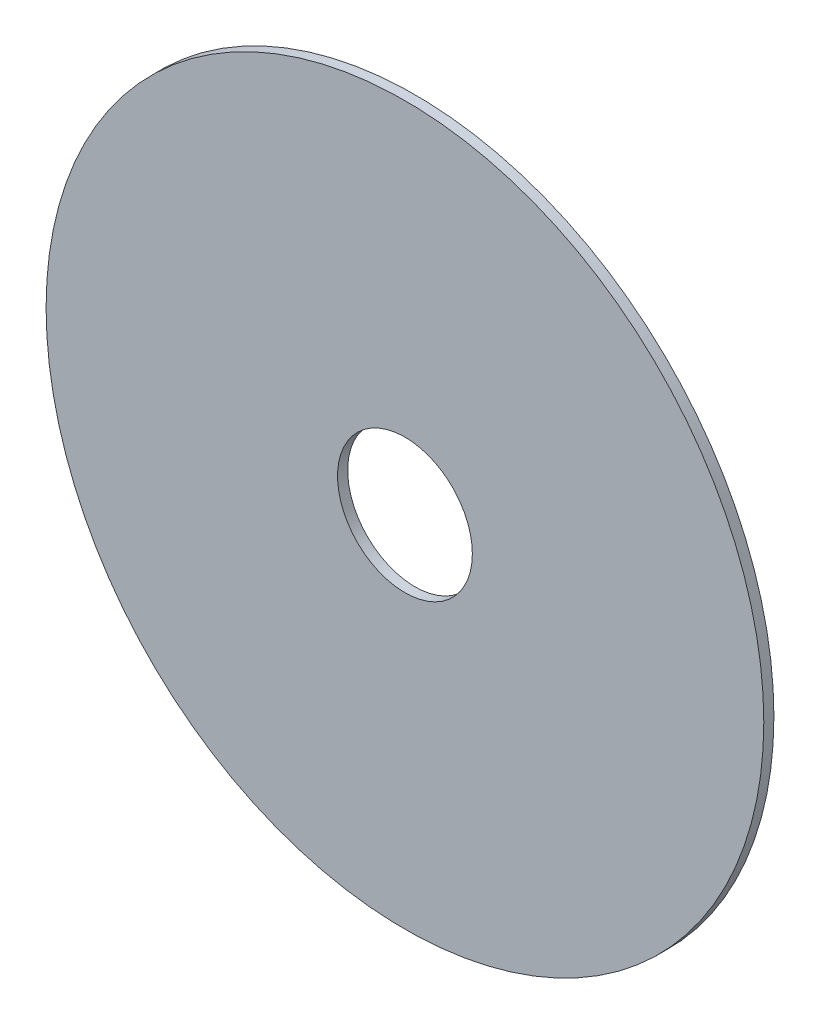
SolidWorks part; units mm, degrees
ref_plane "Alzado" through (0, 0, 0) normal (0, 0, 1) x (1, 0, 0)
ref_plane "Planta" through (0, 0, 0) normal (0, 1, 0) x (1, 0, 0)
ref_plane "Vista lateral" through (0, 0, 0) normal (1, 0, 0) x (0, 0, -1)
sketch "Croquis1" plane through (0, 0, 0) normal (0, 0, 1) x (1, 0, 0)
  circle A0 centre (0, 0) radius 106.5
  circle A1 centre (0, 0) radius 20
  dimension "D1" = 213
  dimension "D2" = 40
extrude "Saliente-Extruir1" add sketch "Croquis1" along normal blind 3
